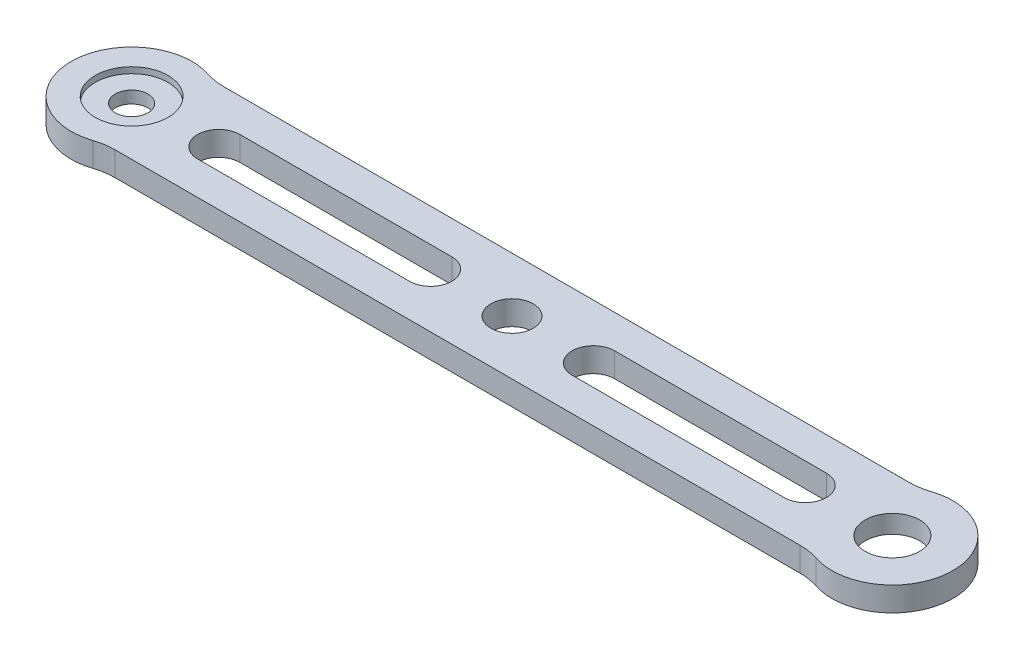
SolidWorks part; units mm, degrees
material "6061 合金"
ref_plane "前视基准面" through (0, 0, 0) normal (0, 0, 1) x (1, 0, 0)
ref_plane "上视基准面" through (0, 0, 0) normal (0, 1, 0) x (1, 0, 0)
ref_plane "右视基准面" through (0, 0, 0) normal (1, 0, 0) x (0, 0, -1)
other "Configuration Table"
sketch "草图1" plane through (0, 0, 0) normal (0, 1, 0) x (1, 0, 0)
  line L0 (0, 0) -> (125.6709, 0) construction
  line L39 (4.3589, -9) -> (121.312, -9)
  line L40 (62.8355, 0) -> (62.8355, 19.5376) construction
  line L41 (4.3589, 9) -> (121.312, 9)
  line L42 (49.3955, 0) -> (14.3955, 0) construction
  line L43 (49.3955, -3.5) -> (14.3955, -3.5)
  line L44 (49.3955, 3.5) -> (14.3955, 3.5)
  line L45 (76.2754, 0) -> (111.2754, 0) construction
  line L46 (76.2754, -3.5) -> (111.2754, -3.5)
  line L47 (76.2754, 3.5) -> (111.2754, 3.5)
  circle A2 centre (0, 0) radius 2.7
  circle A3 centre (125.6709, 0) radius 2.5
  arc A7 (4.3589, 9) -> (4.3589, -9) centre (0, 0) ccw
  arc A8 (121.312, 9) -> (121.312, -9) centre (125.6709, 0) cw
  arc A9 (49.3955, -3.5) -> (49.3955, 3.5) centre (49.3955, 0) ccw
  arc A10 (14.3955, 3.5) -> (14.3955, -3.5) centre (14.3955, 0) ccw
  arc A11 (76.2754, -3.5) -> (76.2754, 3.5) centre (76.2754, 0) cw
  arc A12 (111.2754, 3.5) -> (111.2754, -3.5) centre (111.2754, 0) cw
  circle A13 centre (62.8355, 0) radius 3.5
  point P5 (62.8355, 0)
  point P12 (62.8355, 0)
  point P13 (31.8955, 0)
  point P23 (93.7754, 0)
extrude "凸台-拉伸1" add sketch "草图1" along normal blind 4
sketch "草图2" plane through (0, 0, 0) normal (0, -1, 0) x (1, 0, 0)
  circle A0 centre (125.6709, 0) radius 6.01
extrude "切除-拉伸1" cut sketch "草图2" against normal blind 1
sketch "草图3" plane through (0, 4, 0) normal (0, 1, 0) x (1, 0, 0)
  circle A0 centre (0, 0) radius 6.01
extrude "切除-拉伸2" cut sketch "草图3" against normal blind 1
sketch "草图4" plane through (0, 0, 0) normal (0, -1, 0) x (1, 0, 0)
  circle A0 centre (0, 0) radius 6.01
extrude "切除-拉伸3" cut sketch "草图4" against normal blind 1
sketch "草图5" plane through (0, 4, 0) normal (0, 1, 0) x (1, 0, 0)
  circle A0 centre (125.6709, 0) radius 4.505
extrude "切除-拉伸4" cut sketch "草图5" against normal through all
fillet "圆角1" radius 10 4 edges at (4.3589, 2, -9) (121.312, 2, -9) (121.312, 2, 9) (4.3589, 2, 9)
ref_point "点1"
